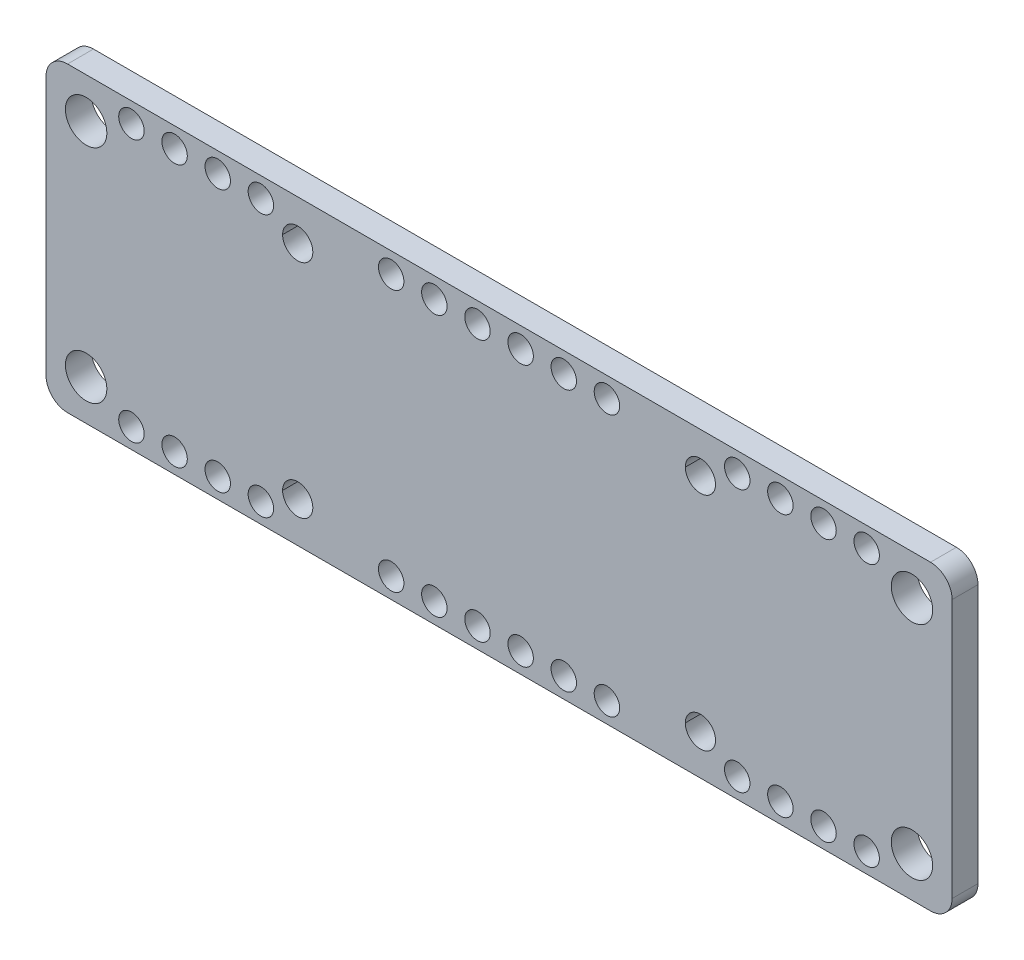
SolidWorks part; units mm, degrees
ref_plane "Front Plane" through (0, 0, 0) normal (0, 0, 1) x (1, 0, 0)
ref_plane "Top Plane" through (0, 0, 0) normal (0, 1, 0) x (1, 0, 0)
ref_plane "Right Plane" through (0, 0, 0) normal (1, 0, 0) x (0, 0, -1)
sketch "Sketch1" plane through (0, 0, 0) normal (0, 0, 1) x (1, 0, 0)
  line L0 (-13.8111, 3.9688) -> (-20.3306, -2.5504) construction
  line L1 (3.9688, 3.9688) -> (-3.9688, -3.9688) construction
  line L2 (20.3311, 2.5506) -> (13.8114, -3.9688) construction
  line L3 (-13.8111, -3.9688) -> (-20.3306, 2.5506) construction
  line L4 (3.9688, -3.9688) -> (-3.9688, 3.9688) construction
  line L5 (20.3311, -2.5504) -> (13.8114, 3.9688) construction
  line L6 (-26.6699, -7.6202) -> (-26.6699, 7.62)
  line L7 (-18.4147, -4.9606) -> (-18.4147, 3.5858)
  line L8 (-17.7798, -6.1454) -> (-17.7798, 6.145) construction
  line L10 (-15.4871, 6.8883) -> (-15.8078, 5.9245) construction
  line L11 (-20.0725, -6.8885) -> (-19.7514, -5.9249) construction
  line L12 (-20.0725, 6.8883) -> (-19.7514, 5.9245) construction
  line L13 (-15.4871, -6.8885) -> (-15.8078, -5.9249) construction
  line L14 (-9.1671, -8.4122) -> (-9.1671, 8.4121) construction
  line L15 (-8.8897, -7.6202) -> (-8.8897, 7.62) construction
  line L16 (-8.6124, -8.4122) -> (-8.6124, 8.4121) construction
  line L17 (25.4002, -8.8901) -> (10.1603, -8.8901)
  line L18 (7.6202, -8.8901) -> (-7.6199, -8.8901)
  line L19 (-10.1599, -8.8901) -> (-25.4, -8.8901)
  line L20 (-18.4147, -4.9606) -> (-17.5227, -5.3184) construction
  line L21 (22.7413, -0.6349) -> (12.8199, -0.6349)
  line L22 (11.6348, 0) -> (23.9246, -0.0003) construction
  line L23 (12.8199, 0.6351) -> (22.7413, 0.6351)
  line L24 (24.6691, 2.2924) -> (23.7045, 1.9716) construction
  line L27 (24.6686, -2.2925) -> (23.7619, -1.9911) construction
  line L28 (10.8913, 2.2924) -> (11.8556, 1.9716) construction
  line L29 (8.6127, -8.4122) -> (8.6127, 8.4121) construction
  line L30 (8.8901, -7.6202) -> (8.8901, 7.62) construction
  line L31 (9.1674, -8.4122) -> (9.1674, 8.4121) construction
  line L32 (-25.4, 8.8901) -> (-10.1599, 8.8901)
  line L33 (-7.6199, 8.8901) -> (7.6202, 8.8901)
  line L34 (10.1603, 8.8901) -> (25.4002, 8.8901)
  line L35 (12.8199, -0.6349) -> (12.8199, 0.6351) construction
  line L36 (22.7413, -0.6349) -> (22.7413, 0.6351) construction
  line L37 (26.6701, 7.62) -> (26.6701, -7.6202)
  spline S0 degree 3 poles (-17.7798, -6.1454) (-17.261, -6.8685) (-16.3318, -7.1696) (-15.4871, -6.8892) knots 0 0 0 0 1 1 1 1 construction
  spline S1 degree 3 poles (-26.3312, -6.5192) (-26.3312, -7.6419) (-25.4214, -8.5511) (-24.2993, -8.5511) (-23.1769, -8.5511) (-22.267, -7.6419) (-22.267, -6.5192) knots 2 2 2 2 3 3 3 4 4 4 4
  spline S2 degree 3 poles (-22.267, -6.5192) (-22.267, -5.3971) (-23.1769, -4.4872) (-24.2993, -4.4872) (-25.4214, -4.4872) (-26.3312, -5.3971) (-26.3312, -6.5192) knots 0 0 0 0 1 1 1 2 2 2 2
  spline S3 degree 3 poles (-20.0725, -6.8885) (-19.2281, -7.1696) (-18.2986, -6.8685) (-17.7798, -6.1454) knots 0 0 0 0 1 1 1 1 construction
  spline S4 degree 3 poles (-8.8897, -7.6202) (-8.8897, -8.3216) (-8.3213, -8.8901) (-7.6199, -8.8901) knots 0 0 0 0 1 1 1 1
  spline S5 degree 3 poles (-10.1599, -8.8901) (-9.4585, -8.8901) (-8.8897, -8.3216) (-8.8897, -7.6202) knots 0 0 0 0 1 1 1 1
  spline S6 degree 3 poles (-26.6699, -7.6202) (-26.6699, -8.3216) (-26.1011, -8.8901) (-25.4, -8.8901) knots 0 0 0 0 1 1 1 1
  spline S7 degree 3 poles (-25.3787, -6.5192) (-25.3787, -7.1155) (-24.8953, -7.5989) (-24.2993, -7.5989) (-23.703, -7.5989) (-23.2196, -7.1155) (-23.2196, -6.5192) knots 2 2 2 2 3 3 3 4 4 4 4
  spline S8 degree 3 poles (-23.2196, -6.5192) (-23.2196, -5.9232) (-23.703, -5.4398) (-24.2993, -5.4398) (-24.8953, -5.4398) (-25.3787, -5.9232) (-25.3787, -6.5192) knots 0 0 0 0 1 1 1 2 2 2 2
  spline S9 degree 3 poles (-18.8364, -5.7847) (-18.5718, -5.5938) (-18.4147, -5.2872) (-18.4147, -4.9606) knots 0 0 0 0 1 1 1 1
  spline S10 degree 3 poles (-19.7514, -5.9249) (-19.4417, -6.0279) (-19.1013, -5.9755) (-18.8364, -5.7847) knots 0 0 0 0 1 1 1 1
  spline S11 degree 3 poles (-16.7228, -5.7847) (-16.4583, -5.9755) (-16.1179, -6.0279) (-15.8078, -5.9249) knots 0 0 0 0 1 1 1 1
  spline S13 degree 3 poles (-6.8154, -6.5192) (-6.8154, -7.0104) (-6.4175, -7.4083) (-5.9266, -7.4083) (-5.4353, -7.4083) (-5.0374, -7.0104) (-5.0374, -6.5192) knots 2 2 2 2 3 3 3 4 4 4 4 construction
  spline S14 degree 3 poles (-5.0374, -6.5192) (-5.0374, -6.0286) (-5.4353, -5.6307) (-5.9266, -5.6307) (-6.4175, -5.6307) (-6.8154, -6.0286) (-6.8154, -6.5192) knots 0 0 0 0 1 1 1 2 2 2 2 construction
  spline S15 degree 3 poles (-12.742, -6.5192) (-12.742, -7.0104) (-12.3441, -7.4083) (-11.8532, -7.4083) (-11.3619, -7.4083) (-10.964, -7.0104) (-10.964, -6.5192) knots 2 2 2 2 3 3 3 4 4 4 4 construction
  spline S16 degree 3 poles (-10.964, -6.5192) (-10.964, -6.0286) (-11.3619, -5.6307) (-11.8532, -5.6307) (-12.3441, -5.6307) (-12.742, -6.0286) (-12.742, -6.5192) knots 0 0 0 0 1 1 1 2 2 2 2 construction
  spline S17 degree 3 poles (-15.4871, 6.8883) (-12.5209, 5.9013) (-10.5196, 3.1261) (-10.5196, 0) knots 0 0 0 0 1 1 1 1 construction
  spline S18 degree 3 poles (-10.5196, 0) (-10.5196, -3.1264) (-12.5209, -5.9018) (-15.4871, -6.8885) knots 0 0 0 0 1 1 1 1 construction
  spline S19 degree 3 poles (-25.04, 0) (-25.04, -3.1264) (-23.0387, -5.9018) (-20.0725, -6.8885) knots 0 0 0 0 1 1 1 1 construction
  spline S20 degree 3 poles (-20.0725, 6.8883) (-23.0387, 5.9013) (-25.04, 3.1261) (-25.04, 0) knots 0 0 0 0 1 1 1 1 construction
  spline S21 degree 3 poles (-15.8078, 5.9245) (-13.2567, 5.0755) (-11.5356, 2.6886) (-11.5356, 0) knots 0 0 0 0 1 1 1 1
  spline S22 degree 3 poles (-11.5356, 0) (-11.5356, -2.6889) (-13.2567, -5.0757) (-15.8078, -5.9249) knots 0 0 0 0 1 1 1 1
  spline S23 degree 3 poles (-24.024, 0) (-24.024, -2.6889) (-22.3029, -5.0757) (-19.7514, -5.9249) knots 0 0 0 0 1 1 1 1
  spline S24 degree 3 poles (-19.7514, 5.9245) (-22.3029, 5.0755) (-24.024, 2.6886) (-24.024, 0) knots 0 0 0 0 1 1 1 1
  spline S25 degree 3 poles (-17.7798, 6.145) (-18.2986, 6.8683) (-19.2281, 7.1699) (-20.0725, 6.8886) knots 0 0 0 0 1 1 1 1 construction
  spline S26 degree 3 poles (-26.3312, 6.5193) (-26.3312, 5.3967) (-25.4214, 4.4874) (-24.2993, 4.4874) (-23.1769, 4.4874) (-22.267, 5.3967) (-22.267, 6.5193) knots 2 2 2 2 3 3 3 4 4 4 4
  spline S27 degree 3 poles (-22.267, 6.5193) (-22.267, 7.6416) (-23.1769, 8.5514) (-24.2993, 8.5514) (-25.4214, 8.5514) (-26.3312, 7.6416) (-26.3312, 6.5193) knots 0 0 0 0 1 1 1 2 2 2 2
  spline S28 degree 3 poles (-15.4871, 6.8883) (-16.3318, 7.1696) (-17.261, 6.8683) (-17.7798, 6.145) knots 0 0 0 0 1 1 1 1 construction
  spline S29 degree 3 poles (-7.6199, 8.8901) (-8.3213, 8.8901) (-8.8897, 8.3213) (-8.8897, 7.62) knots 0 0 0 0 1 1 1 1
  spline S30 degree 3 poles (-25.4, 8.8901) (-26.1011, 8.8901) (-26.6699, 8.3213) (-26.6699, 7.62) knots 0 0 0 0 1 1 1 1
  spline S31 degree 3 poles (-8.8897, 7.62) (-8.8897, 8.3213) (-9.4585, 8.8901) (-10.1599, 8.8901) knots 0 0 0 0 1 1 1 1
  spline S34 degree 3 poles (-18.8364, 5.7845) (-19.1013, 5.9757) (-19.4417, 6.0275) (-19.7514, 5.9245) knots 0 0 0 0 1 1 1 1
  spline S35 degree 3 poles (-18.4147, 3.5858) (-18.1937, 4.3446) (-18.3512, 5.1624) (-18.8364, 5.7845) knots 0 0 0 0 1 1 1 1
  spline S36 degree 3 poles (-12.742, 6.5193) (-12.742, 6.0282) (-12.3441, 5.6303) (-11.8532, 5.6303) (-11.3619, 5.6303) (-10.964, 6.0282) (-10.964, 6.5193) knots 2 2 2 2 3 3 3 4 4 4 4 construction
  spline S37 degree 3 poles (-10.964, 6.5193) (-10.964, 7.0101) (-11.3619, 7.408) (-11.8532, 7.408) (-12.3441, 7.408) (-12.742, 7.0101) (-12.742, 6.5193) knots 0 0 0 0 1 1 1 2 2 2 2 construction
  spline S38 degree 3 poles (-6.8154, 6.5193) (-6.8154, 6.0282) (-6.4175, 5.6303) (-5.9266, 5.6303) (-5.4353, 5.6303) (-5.0374, 6.0282) (-5.0374, 6.5193) knots 2 2 2 2 3 3 3 4 4 4 4 construction
  spline S39 degree 3 poles (-5.0374, 6.5193) (-5.0374, 7.0101) (-5.4353, 7.408) (-5.9266, 7.408) (-6.4175, 7.408) (-6.8154, 7.0101) (-6.8154, 6.5193) knots 0 0 0 0 1 1 1 2 2 2 2 construction
  spline S40 degree 3 poles (11.6348, 0) (10.9117, -0.5188) (10.6102, -1.448) (10.8913, -2.2931) knots 0 0 0 0 1 1 1 1 construction
  spline S41 degree 3 poles (22.2672, -6.5192) (22.2672, -7.6419) (23.1774, -8.5511) (24.2998, -8.5511) (25.4215, -8.5511) (26.3317, -7.6419) (26.3317, -6.5192) knots 2 2 2 2 3 3 3 4 4 4 4
  spline S42 degree 3 poles (26.3317, -6.5192) (26.3317, -5.3971) (25.4215, -4.4872) (24.2998, -4.4872) (23.1774, -4.4872) (22.2672, -5.3971) (22.2672, -6.5192) knots 0 0 0 0 1 1 1 2 2 2 2
  spline S43 degree 3 poles (23.9246, -0.0003) (24.6475, -0.519) (24.9495, -1.4477) (24.6686, -2.2925) knots 0 0 0 0 1 1 1 1 construction
  spline S44 degree 3 poles (25.4002, -8.8901) (26.1016, -8.8901) (26.6701, -8.3216) (26.6701, -7.6202) knots 0 0 0 0 1 1 1 1
  spline S45 degree 3 poles (8.8901, -7.6202) (8.8901, -8.3216) (9.4589, -8.8901) (10.1603, -8.8901) knots 0 0 0 0 1 1 1 1
  spline S46 degree 3 poles (7.6202, -8.8901) (8.3216, -8.8901) (8.8901, -8.3216) (8.8901, -7.6202) knots 0 0 0 0 1 1 1 1
  spline S47 degree 3 poles (23.2201, -6.5192) (23.2201, -7.1155) (23.7031, -7.5989) (24.2998, -7.5989) (24.8958, -7.5989) (25.3788, -7.1155) (25.3788, -6.5192) knots 2 2 2 2 3 3 3 4 4 4 4
  spline S48 degree 3 poles (25.3788, -6.5192) (25.3788, -5.9232) (24.8958, -5.4398) (24.2998, -5.4398) (23.7031, -5.4398) (23.2201, -5.9232) (23.2201, -6.5192) knots 0 0 0 0 1 1 1 2 2 2 2
  spline S49 degree 3 poles (22.7413, -0.6349) (23.0669, -0.6485) (23.3667, -0.8182) (23.5471, -1.0908) knots 0 0 0 0 1 1 1 1
  spline S50 degree 3 poles (23.5471, -1.0908) (23.7593, -1.3389) (23.8392, -1.6738) (23.7619, -1.9911) knots 0 0 0 0 1 1 1 1
  spline S51 degree 3 poles (11.9994, -1.0639) (11.8137, -1.3327) (11.7687, -1.674) (11.878, -1.9816) knots 0 0 0 0 1 1 1 1
  spline S52 degree 3 poles (12.8199, -0.6349) (12.493, -0.6377) (12.188, -0.7973) (11.9994, -1.0639) knots 0 0 0 0 1 1 1 1
  spline S53 degree 3 poles (5.0378, -6.5192) (5.0378, -7.0104) (5.4357, -7.4083) (5.9269, -7.4083) (6.4179, -7.4083) (6.8158, -7.0104) (6.8158, -6.5192) knots 2 2 2 2 3 3 3 4 4 4 4 construction
  spline S54 degree 3 poles (6.8158, -6.5192) (6.8158, -6.0286) (6.4179, -5.6307) (5.9269, -5.6307) (5.4357, -5.6307) (5.0378, -6.0286) (5.0378, -6.5192) knots 0 0 0 0 1 1 1 2 2 2 2 construction
  spline S55 degree 3 poles (10.9644, -6.5192) (10.9644, -7.0104) (11.3626, -7.4083) (11.8535, -7.4083) (12.3445, -7.4083) (12.7424, -7.0104) (12.7424, -6.5192) knots 2 2 2 2 3 3 3 4 4 4 4 construction
  spline S56 degree 3 poles (12.7424, -6.5192) (12.7424, -6.0286) (12.3445, -5.6307) (11.8535, -5.6307) (11.3626, -5.6307) (10.9644, -6.0286) (10.9644, -6.5192) knots 0 0 0 0 1 1 1 2 2 2 2 construction
  spline S57 degree 3 poles (-7.2599, 0) (-7.2599, -4.0097) (-4.0094, -7.2602) (0, -7.2602) (4.0097, -7.2602) (7.2602, -4.0097) (7.2602, 0) knots 2 2 2 2 3 3 3 4 4 4 4 construction
  spline S58 degree 3 poles (7.2602, 0) (7.2602, 4.0097) (4.0097, 7.2602) (0, 7.2602) (-4.0094, 7.2602) (-7.2599, 4.0097) (-7.2599, 0) knots 0 0 0 0 1 1 1 2 2 2 2 construction
  spline S59 degree 3 poles (17.7799, -7.2602) (14.6533, -7.26) (11.8787, -5.259) (10.8912, -2.2923) knots 0 0 0 0 1 1 1 1 construction
  spline S60 degree 3 poles (17.78, -6.2446) (15.0912, -6.2444) (12.7046, -4.5231) (11.8555, -1.9716) knots 0 0 0 0 1 1 1 1
  spline S61 degree 3 poles (17.7803, 7.2599) (14.6537, 7.2599) (11.879, 5.2589) (10.8913, 2.2924) knots 0 0 0 0 1 1 1 1 construction
  spline S62 degree 3 poles (24.6691, 2.2924) (23.6818, 5.2589) (20.9064, 7.2599) (17.7803, 7.2599) knots 0 0 0 0 1 1 1 1 construction
  spline S63 degree 3 poles (23.7044, -1.9723) (22.8554, -4.5237) (20.4685, -6.2447) (17.78, -6.2446) knots 0 0 0 0 1 1 1 1
  spline S64 degree 3 poles (24.669, -2.2931) (23.6815, -5.2596) (20.906, -7.2604) (17.7799, -7.2602) knots 0 0 0 0 1 1 1 1 construction
  spline S65 degree 3 poles (17.7803, 6.2442) (15.0916, 6.2442) (12.7048, 4.5231) (11.8556, 1.9716) knots 0 0 0 0 1 1 1 1
  spline S66 degree 3 poles (23.7045, 1.9716) (22.8556, 4.5231) (20.4689, 6.2442) (17.7803, 6.2442) knots 0 0 0 0 1 1 1 1
  spline S67 degree 3 poles (24.6691, 2.2924) (24.9499, 1.4473) (24.6476, 0.5183) (23.9246, -0.0003) knots 0 0 0 0 1 1 1 1 construction
  spline S68 degree 3 poles (22.2672, 6.5193) (22.2672, 5.3967) (23.1774, 4.4874) (24.2998, 4.4874) (25.4215, 4.4874) (26.3317, 5.3967) (26.3317, 6.5193) knots 2 2 2 2 3 3 3 4 4 4 4
  spline S69 degree 3 poles (26.3317, 6.5193) (26.3317, 7.6416) (25.4215, 8.5514) (24.2998, 8.5514) (23.1774, 8.5514) (22.2672, 7.6416) (22.2672, 6.5193) knots 0 0 0 0 1 1 1 2 2 2 2
  spline S70 degree 3 poles (10.8913, 2.2924) (10.6106, 1.4478) (10.912, 0.519) (11.6351, 0) knots 0 0 0 0 1 1 1 1 construction
  spline S71 degree 3 poles (8.8901, 7.62) (8.8901, 8.3213) (8.3216, 8.8901) (7.6202, 8.8901) knots 0 0 0 0 1 1 1 1
  spline S72 degree 3 poles (10.1603, 8.8901) (9.4589, 8.8901) (8.8901, 8.3213) (8.8901, 7.62) knots 0 0 0 0 1 1 1 1
  spline S73 degree 3 poles (26.6701, 7.62) (26.6701, 8.3213) (26.1016, 8.8901) (25.4002, 8.8901) knots 0 0 0 0 1 1 1 1
  spline S74 degree 3 poles (23.2201, 6.5193) (23.2201, 5.9232) (23.7031, 5.4398) (24.2998, 5.4398) (24.8958, 5.4398) (25.3788, 5.9232) (25.3788, 6.5193) knots 2 2 2 2 3 3 3 4 4 4 4
  spline S75 degree 3 poles (25.3788, 6.5193) (25.3788, 7.1155) (24.8958, 7.5989) (24.2998, 7.5989) (23.7031, 7.5989) (23.2201, 7.1155) (23.2201, 6.5193) knots 0 0 0 0 1 1 1 2 2 2 2
  spline S76 degree 3 poles (23.7045, 1.9716) (23.8079, 1.6619) (23.7562, 1.3215) (23.5653, 1.0566) knots 0 0 0 0 1 1 1 1
  spline S77 degree 3 poles (23.5653, 1.0566) (23.3738, 0.7917) (23.0672, 0.6351) (22.7413, 0.6351) knots 0 0 0 0 1 1 1 1
  spline S78 degree 3 poles (11.9958, 1.0566) (12.1867, 0.7917) (12.493, 0.6351) (12.8199, 0.6351) knots 0 0 0 0 1 1 1 1
  spline S79 degree 3 poles (11.8556, 1.9716) (11.7526, 1.6619) (11.8046, 1.3215) (11.9958, 1.0566) knots 0 0 0 0 1 1 1 1
  spline S80 degree 3 poles (10.9644, 6.5193) (10.9644, 6.0282) (11.3626, 5.6303) (11.8535, 5.6303) (12.3445, 5.6303) (12.7424, 6.0282) (12.7424, 6.5193) knots 2 2 2 2 3 3 3 4 4 4 4 construction
  spline S81 degree 3 poles (12.7424, 6.5193) (12.7424, 7.0101) (12.3445, 7.408) (11.8535, 7.408) (11.3626, 7.408) (10.9644, 7.0101) (10.9644, 6.5193) knots 0 0 0 0 1 1 1 2 2 2 2 construction
  spline S82 degree 3 poles (5.0378, 6.5193) (5.0378, 6.0282) (5.4357, 5.6303) (5.9269, 5.6303) (6.4179, 5.6303) (6.8158, 6.0282) (6.8158, 6.5193) knots 2 2 2 2 3 3 3 4 4 4 4 construction
  spline S83 degree 3 poles (6.8158, 6.5193) (6.8158, 7.0101) (6.4179, 7.408) (5.9269, 7.408) (5.4357, 7.408) (5.0378, 7.0101) (5.0378, 6.5193) knots 0 0 0 0 1 1 1 2 2 2 2 construction
  spline S84 degree 3 poles (-6.2439, 0) (-6.2439, -3.4489) (-3.4482, -6.2442) (0, -6.2442) (3.4489, -6.2442) (6.2442, -3.4489) (6.2442, 0) knots 2 2 2 2 3 3 3 4 4 4 4
  spline S85 degree 3 poles (6.2442, 0) (6.2442, 3.4484) (3.4489, 6.2442) (0, 6.2442) (-3.4482, 6.2442) (-6.2439, 3.4484) (-6.2439, 0) knots 0 0 0 0 1 1 1 2 2 2 2
  point P123 (0, 0)
sketch "Sketch2" plane through (0, 0, 0) normal (0, 0, 1) x (1, 0, 0)
  line L0 (-7.6199, 8.8901) -> (7.6202, 8.8901) construction
  line L1 (26.67, -8.8901) -> (-26.67, -8.8901)
  line L2 (26.67, -8.8901) -> (26.67, 8.8901)
  line L3 (26.67, 8.8901) -> (-26.67, 8.8901)
  line L4 (-26.67, -8.8901) -> (-26.67, 8.8901)
  line L5 (26.67, -8.8901) -> (-26.67, 8.8901) construction
  line L6 (26.67, 8.8901) -> (-26.67, -8.8901) construction
  point P0 (0, 0)
  dimension "D1" = 53.34
  dimension "D2" = 17.7801
extrude "Boss-Extrude1" add sketch "Sketch2" against normal blind 1.524
sketch "Sketch3" plane through (0, 0, 0) normal (0, 0, 1) x (1, 0, 0)
  spline S0 degree 3 poles (-1612.8777, 1201.4777) (-22.5244, -110.0065) (-3.4142, 7.408) (-11.8532, 7.408) (-20.2846, 7.408) (-1.2791, -109.9612) (1589.7088, 1200.7185) knots -16.177862 -16.177862 -16.177862 -16.177862 1 1 1 18.174547 18.174547 18.174547 18.174547 only from (-10.964, 6.5193) to (-12.742, 6.5193) construction
  spline S1 degree 3 poles (1590.5445, -1186.6225) (-1.2725, 123.0406) (-20.2861, 5.6303) (-11.8532, 5.6303) (-3.4129, 5.6303) (-22.5306, 123.0829) (-1613.6505, -1187.3296) knots -14.177554 -14.177554 -14.177554 -14.177554 3 3 3 20.180644 20.180644 20.180644 20.180644 only from (-12.742, 6.5193) to (-10.964, 6.5193) construction
  spline S4 degree 3 poles (-1612.4844, 1188.9876) (-22.5213, -123.0258) (-3.4149, -5.6307) (-11.8532, -5.6307) (-20.2839, -5.6307) (-1.2824, -122.9798) (1589.3017, 1188.2169) knots -16.176446 -16.176446 -16.176446 -16.176446 1 1 1 18.173082 18.173082 18.173082 18.173082 only from (-10.964, -6.5192) to (-12.742, -6.5192) construction
  spline S5 degree 3 poles (1590.9329, -1199.1074) (-1.2694, 110.0211) (-20.2868, -7.4083) (-11.8532, -7.4083) (-3.4121, -7.4083) (-22.5339, 110.064) (-1614.053, -1199.826) knots -14.178951 -14.178951 -14.178951 -14.178951 3 3 3 20.182093 20.182093 20.182093 20.182093 only from (-12.742, -6.5192) to (-10.964, -6.5192) construction
  spline S12 degree 3 poles (-1589.2989, 1188.2148) (1.2827, -122.9797) (20.2843, -5.6307) (11.8535, -5.6307) (3.4263, -5.6307) (22.3072, -122.8832) (1614.2253, 1186.598) knots -16.173073 -16.173073 -16.173073 -16.173073 1 1 1 18.166011 18.166011 18.166011 18.166011 only from (12.7424, -6.5192) to (10.9644, -6.5192) construction
  spline S13 degree 3 poles (1615.8526, -1197.4868) (22.3201, 109.9241) (3.4234, -7.4083) (11.8535, -7.4083) (20.2872, -7.4083) (1.2696, 110.0218) (-1590.9473, -1199.1196) knots -14.171859 -14.171859 -14.171859 -14.171859 3 3 3 20.179004 20.179004 20.179004 20.179004 only from (10.9644, -6.5192) to (12.7424, -6.5192) construction
  spline S14 degree 3 poles (-1589.757, 1200.7585) (1.2791, -109.9636) (20.2851, 7.408) (11.8535, 7.408) (3.4256, 7.408) (22.3105, -109.8647) (1614.636, 1199.1029) knots -16.174722 -16.174722 -16.174722 -16.174722 1 1 1 18.167487 18.167487 18.167487 18.167487 only from (12.7424, 6.5193) to (10.9644, 6.5193) construction
  spline S15 degree 3 poles (1615.4637, -1185.0011) (22.317, 122.9437) (3.4241, 5.6303) (11.8535, 5.6303) (20.2865, 5.6303) (1.2728, 123.0406) (-1590.5445, -1186.6228) knots -14.170462 -14.170462 -14.170462 -14.170462 3 3 3 20.177555 20.177555 20.177555 20.177555 only from (10.9644, 6.5193) to (12.7424, 6.5193) construction
  spline S16 degree 3 poles (-10.964, 6.5193) (-10.964, 7.0101) (-11.3619, 7.408) (-11.8532, 7.408) (-12.3441, 7.408) (-12.742, 7.0101) (-12.742, 6.5193) knots 0 0 0 0 1 1 1 2 2 2 2
  spline S17 degree 3 poles (-12.742, 6.5193) (-12.742, 6.0282) (-12.3441, 5.6303) (-11.8532, 5.6303) (-11.3619, 5.6303) (-10.964, 6.0282) (-10.964, 6.5193) knots 2 2 2 2 3 3 3 4 4 4 4
  spline S20 degree 3 poles (-10.964, -6.5192) (-10.964, -6.0286) (-11.3619, -5.6307) (-11.8532, -5.6307) (-12.3441, -5.6307) (-12.742, -6.0286) (-12.742, -6.5192) knots 0 0 0 0 1 1 1 2 2 2 2
  spline S21 degree 3 poles (-12.742, -6.5192) (-12.742, -7.0104) (-12.3441, -7.4083) (-11.8532, -7.4083) (-11.3619, -7.4083) (-10.964, -7.0104) (-10.964, -6.5192) knots 2 2 2 2 3 3 3 4 4 4 4
  spline S28 degree 3 poles (12.7424, -6.5192) (12.7424, -6.0286) (12.3445, -5.6307) (11.8535, -5.6307) (11.3626, -5.6307) (10.9644, -6.0286) (10.9644, -6.5192) knots 0 0 0 0 1 1 1 2 2 2 2
  spline S29 degree 3 poles (10.9644, -6.5192) (10.9644, -7.0104) (11.3626, -7.4083) (11.8535, -7.4083) (12.3445, -7.4083) (12.7424, -7.0104) (12.7424, -6.5192) knots 2 2 2 2 3 3 3 4 4 4 4
  spline S30 degree 3 poles (12.7424, 6.5193) (12.7424, 7.0101) (12.3445, 7.408) (11.8535, 7.408) (11.3626, 7.408) (10.9644, 7.0101) (10.9644, 6.5193) knots 0 0 0 0 1 1 1 2 2 2 2
  spline S31 degree 3 poles (10.9644, 6.5193) (10.9644, 6.0282) (11.3626, 5.6303) (11.8535, 5.6303) (12.3445, 5.6303) (12.7424, 6.0282) (12.7424, 6.5193) knots 2 2 2 2 3 3 3 4 4 4 4
extrude "Cut-Extrude1" cut sketch "Sketch3" against normal up to next
hole_wizard "#2 Clearance Hole1" positions "Sketch5" profile "Sketch4" hole size "#2" standard "Ansi Inch" end condition up to next
sketch "Sketch5" plane through (0, 0, 0) normal (0, 0, 1) x (1, 0, 0)
  line L0 (0, 0) -> (0, 12.8116) construction
  line L2 (0, 0) -> (31.8211, 0) construction
  line L4 (-12.742, 6.5193) -> (-15.3484, 6.5193) construction
  line L6 (-26.6699, -7.6202) -> (-26.6699, 7.62) construction
  point P0 (-24.3077, 6.5193)
  point P1 (-24.3077, -6.5193)
  point P3 (24.3077, -6.5193)
  point P5 (24.3077, 6.5193)
  dimension "D1" = 2.3622
sketch "Sketch4" plane through (-24.3077, 6.5193, 0) normal (1, 0, 0) x (0, -1, 0)
  line L0 (0, 0) -> (0, 1.524)
  line L1 (0, 1.524) -> (1.2192, 1.524)
  line L2 (1.2192, 1.524) -> (1.2192, 0)
  line L5 (1.2192, 0) -> (0, 0)
  line L11 (0, -6.35) -> (0, 107.95) construction
  dimension "Thru Hole Dia." = 2.4384
  dimension "Thru Hole Depth" = 1.524
sketch "Sketch6" plane through (0, 0, 0) normal (0, 0, 1) x (1, 0, 0)
  line L0 (0.8382, 0) -> (-0.8382, 0) construction
  line L1 (0, -0.8382) -> (0, 0.8382) construction
  circle A0 centre (-14.0208, 7.7216) radius 0.7493
  dimension "D1" = 1.4986
  dimension "D2" = 7.7216
  dimension "D3" = 14.0208
extrude "Cut-Extrude2" cut sketch "Sketch6" against normal up to next
pattern_linear "LPattern1" count 4 spacing 2.54 along (-1, 0, 0) of "Cut-Extrude2"
mirror "Mirror1" about plane through (0, 0, 0) normal (1, 0, 0) of "Cut-Extrude2", "LPattern1"
mirror "Mirror2" about plane through (0, 0, 0) normal (0, 1, 0) of "Cut-Extrude2", "LPattern1", "Mirror1"
fillet "Fillet1" radius 1.27 4 edges at (26.67, -8.8901, -0.762) (26.67, 8.8901, -0.762) (-26.67, 8.8901, -0.762) (-26.67, -8.8901, -0.762)
sketch "Sketch7" plane through (0, 0, 0) normal (0, 0, 1) x (1, 0, 0)
  line L0 (0, -0.8382) -> (0, 0.8382) construction
  line L1 (0.8382, 0) -> (-0.8382, 0) construction
  circle A0 centre (6.35, 7.6962) radius 0.7493
  dimension "D1" = 1.4986
  dimension "D2" = 6.35
  dimension "D3" = 7.6962
extrude "Cut-Extrude3" cut sketch "Sketch7" against normal up to next
pattern_linear "LPattern2" count 6 spacing 2.54 along (-1, 0, 0) of "Cut-Extrude3"
mirror "Mirror3" about plane through (0, 0, 0) normal (0, 1, 0) of "Cut-Extrude3", "LPattern2"
